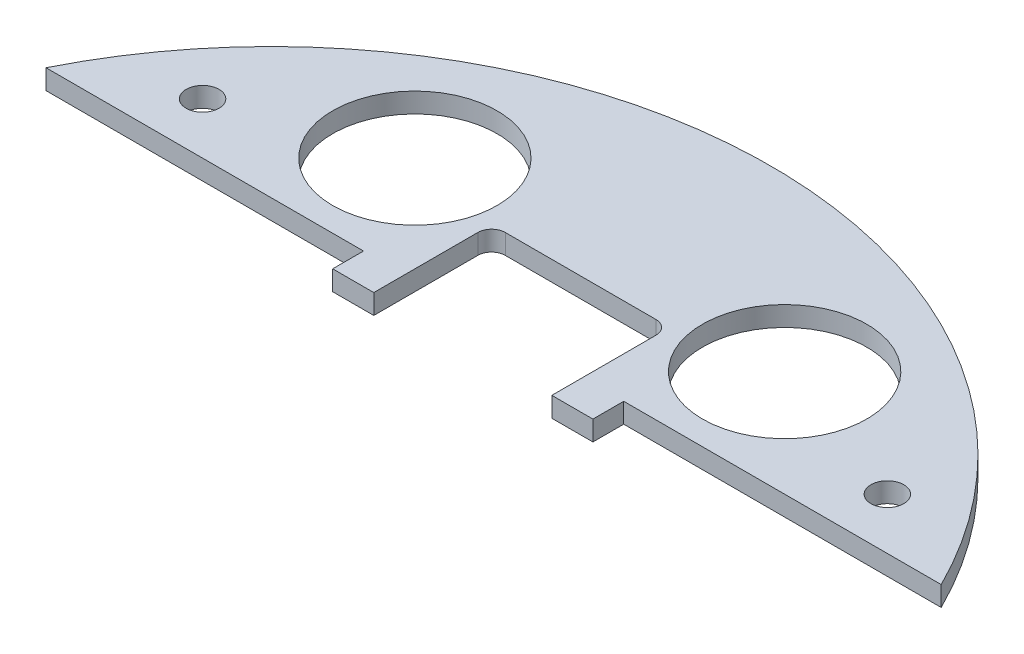
SolidWorks part; units mm, degrees
material "Acrylic (Medium-high impact)"
ref_plane "Front Plane" through (0, 0, 0) normal (0, 0, 1) x (1, 0, 0)
ref_plane "Top Plane" through (0, 0, 0) normal (0, 1, 0) x (1, 0, 0)
ref_plane "Right Plane" through (0, 0, 0) normal (1, 0, 0) x (0, 0, -1)
sketch "Sketch1" plane through (0, 0, 0) normal (0, 1, 0) x (1, 0, 0)
  line L0 (0, -85) -> (-32.7511, -65.2408) construction
  line L1 (0, -85) -> (0, 0) construction
  arc A0 (36.8566, -63.0126) -> (-36.8566, -63.0126) centre (0, 0) ccw
  arc A1 (30.3631, -61.7375) -> (-30.3631, -61.7375) centre (0, -85) ccw
  arc A2 (36.8566, -63.0126) -> (30.3631, -61.7375) centre (34.3322, -58.6967) cw
  arc A3 (-30.3631, -61.7375) -> (-36.8566, -63.0126) centre (-34.3322, -58.6967) cw
  dimension "D1" = 146
  dimension "D2" = 76.5
  dimension "D4" = 5
  dimension "D3" = 85
extrude "Boss-Extrude1" add sketch "Sketch1" along normal blind 2.9
sketch "solenoid placement" plane through (0, 2.9, 0) normal (0, 1, 0) x (1, 0, 0)
  line L4 (-19, -36) -> (19, -36)
  line L5 (-19, 28) -> (-19, -36)
  line L6 (19, 28) -> (-19, 28)
  line L7 (19, -36) -> (19, 28)
  line L8 (-19, -36) -> (19, -36)
  line L9 (-19, 28) -> (-19, -36)
  line L10 (19, 28) -> (-19, 28)
  line L11 (19, -36) -> (19, 28)
  dimension "D1" = 0
extrude "Cut-Extrude1" cut sketch "solenoid placement" against normal through all
sketch "Sketch4" plane through (0, 2.9, 0) normal (0, 1, 0) x (1, 0, 0)
  line L6 (-13, 28) -> (13, 28)
  line L7 (13, 28) -> (13, 43.2)
  line L8 (11, 45.2) -> (-11, 45.2)
  line L9 (-13, 43.2) -> (-13, 28)
  line L10 (-13, 28) -> (13, 28)
  line L11 (13, 28) -> (13, 43.2)
  line L12 (11, 45.2) -> (-11, 45.2)
  line L13 (-13, 43.2) -> (-13, 28)
  arc A4 (13, 43.2) -> (11, 45.2) centre (11, 43.2) ccw
  arc A5 (13, 43.2) -> (11, 45.2) centre (11, 43.2) ccw
  arc A6 (-11, 45.2) -> (-13, 43.2) centre (-11, 43.2) ccw
  arc A7 (-11, 45.2) -> (-13, 43.2) centre (-11, 43.2) ccw
  dimension "D1" = 0
extrude "Cut-Extrude4" cut sketch "Sketch4" against normal through all
sketch "Sketch5" plane through (0, 2.9, 0) normal (0, 1, 0) x (1, 0, 0)
  circle A1 centre (27, 48) radius 12
  circle A2 centre (27, 48) radius 12
  circle A3 centre (-27, 48) radius 12
  circle A4 centre (-27, 48) radius 12
  dimension "D1" = 0
  dimension "D2" = 0
extrude "Cut-Extrude5" cut sketch "Sketch5" against normal through all
sketch "Sketch6" plane through (0, 2.9, 0) normal (0, 1, 0) x (1, 0, 0)
  circle A1 centre (40, -40) radius 2.4
  circle A2 centre (40, -40) radius 2.4
  circle A3 centre (-40, -40) radius 2.4
  circle A4 centre (-40, -40) radius 2.4
  circle A5 centre (-50, 40) radius 2.4
  circle A6 centre (-50, 40) radius 2.4
  circle A7 centre (50, 40) radius 2.4
  circle A8 centre (50, 40) radius 2.4
  dimension "D1" = 0
  dimension "D2" = 0
  dimension "D3" = 0
  dimension "D4" = 0
extrude "Cut-Extrude6" cut sketch "Sketch6" against normal through all
sketch "Sketch7" plane through (0, 2.9, 0) normal (0, 1, 0) x (1, 0, 0)
  line L1 (-5, 0) -> (5, 0)
  line L2 (-5, 0) -> (-5, -62.8025)
  line L3 (-5, -62.8025) -> (5, -62.8025)
  line L4 (5, 0) -> (5, -62.8025)
  dimension "D1" = 10
extrude "Cut-Extrude7" cut sketch "Sketch7" against normal through all
sketch "Sketch3" plane through (0, 2.9, 0) normal (0, 1, 0) x (1, 0, 0)
  line L0 (-19, 28) -> (19, 28)
  line L1 (-73, -32.5) -> (73, -32.5)
  line L2 (-73, -32.5) -> (-73, 32.5)
  line L3 (-73, 32.5) -> (-19, 32.5)
  line L4 (73, -32.5) -> (73, 32.5)
  line L5 (-73, -32.5) -> (73, 32.5) construction
  line L6 (-73, 32.5) -> (73, -32.5) construction
  line L7 (19, 28) -> (19, 32.5)
  line L8 (-19, 28) -> (-19, 32.5)
  line L9 (19, 32.5) -> (73, 32.5)
  arc A0 (36.8566, -63.0126) -> (-36.8566, -63.0126) centre (0, 0) ccw construction
  point P0 (0, 0)
  dimension "D1" = 65
extrude "Cut-Extrude3" cut sketch "Sketch3" against normal through all
delete or keep bodies "Body-Delete/Keep 1" type delete bodies bodies 116 119
equation "\"smallPulleyTeeth\"= 15"
equation "\"largePulleyTeeth\"= 30"
equation "\"eighthThick\"= 2.9mm"
equation "\"sixteenthThick\" = 1.7mm"
equation "\"quarterThick\"=6.0mm"
equation "\"OD\" = 146mm"
equation "\"puckAngle\" = 60.5deg"
equation "\"D1@Sketch1\"=\"OD\""
equation "\"puckDiam\" = 76.5mm"
equation "\"D2@Sketch1\"=\"puckDiam\""
equation "\"D1@Boss-Extrude1\"=\"eighthThick\""
equation "\"axlePress\" = 5.9mm"
equation "\"press\" = 0.2mm"
equation "\"wheelClear\" = 0.3mm"
equation "\"10-32clear\" = 4.8mm"
equation "\"6-32clear\" = 3.3mm"
equation "\"8-32clear\" = 4.0mm"
equation "\"wheelHeight\" = 22mm"
equation "\"wheelWell\" = 65mm"
equation "\"D1@Sketch3\"=\"wheelWell\""
equation "\"puckDist\" = 85mm"
equation "\"scoopFillet\" = 5mm"
equation "\"4-40clear\" = 3.0mm"
equation "\"D3@Sketch1\"=\"puckDist\""
equation "\"D4@Sketch1\"=\"scoopFillet\""
